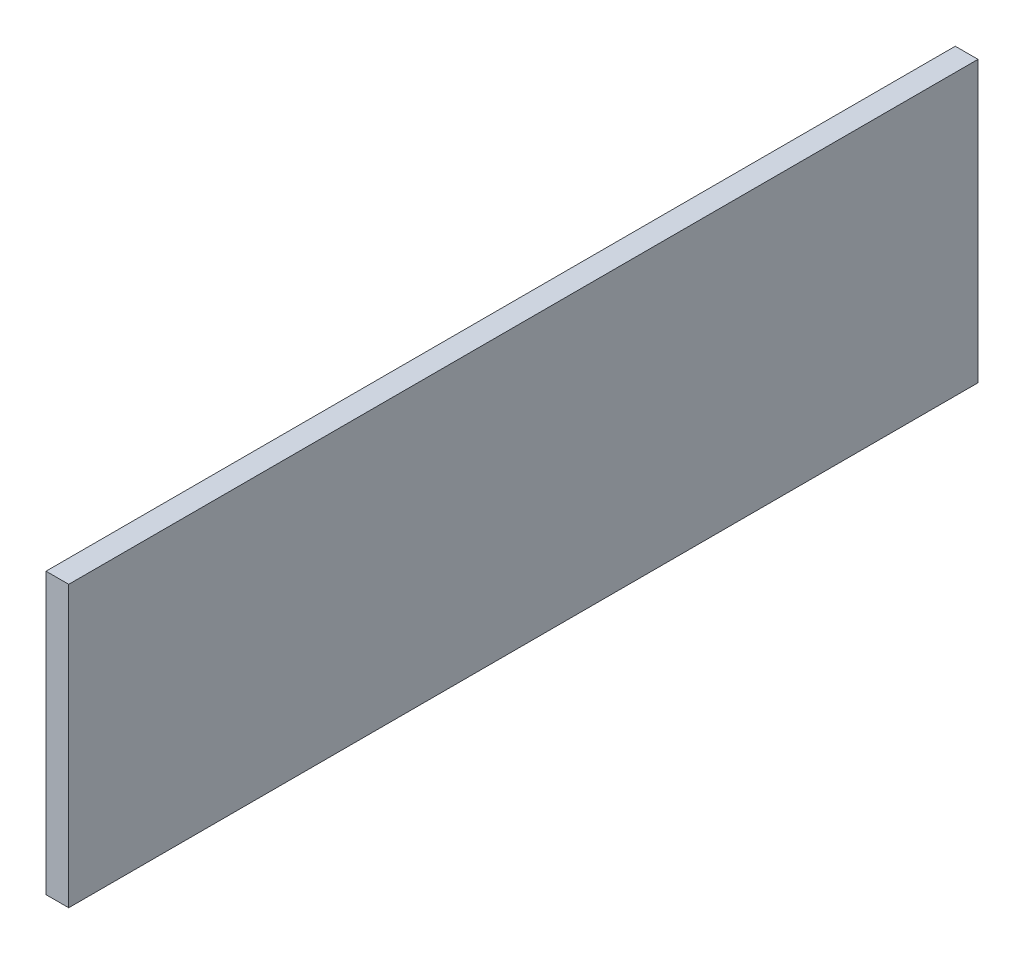
SolidWorks part; units mm, degrees
material "6061-T6 (SS)"
ref_plane "Front" through (0, 0, 0) normal (0, 0, 1) x (1, 0, 0)
ref_plane "Top" through (0, 0, 0) normal (0, 1, 0) x (1, 0, 0)
ref_plane "Right" through (0, 0, 0) normal (1, 0, 0) x (0, 0, -1)
sketch "Sketch1" plane through (0, 0, 0) normal (0, 0, 1) x (1, 0, 0)
  line L0 (-240.475, 9.525) -> (240.475, 9.525)
  line L1 (-250, 0) -> (250, 0)
  line L2 (-250, 0) -> (-250, 500)
  line L3 (-250, 500) -> (250, 500)
  line L4 (250, 0) -> (250, 500)
  line L5 (240.475, 9.525) -> (240.475, 490.475)
  line L6 (-240.475, 490.475) -> (240.475, 490.475)
  line L7 (-240.475, 9.525) -> (-240.475, 490.475)
  line L8 (-142.3043, 490.475) -> (-142.3043, 373.0167) construction
  line L9 (-240.475, 373.0167) -> (240.475, 373.0167)
  line L10 (-240.475, 373.0167) -> (-240.475, 363.4917)
  line L11 (-240.475, 363.4917) -> (240.475, 363.4917)
  line L12 (240.475, 373.0167) -> (240.475, 363.4917)
  line L13 (-240.475, 246.0333) -> (240.475, 246.0333)
  line L14 (-240.475, 246.0333) -> (-240.475, 236.5083)
  line L15 (-240.475, 236.5083) -> (240.475, 236.5083)
  line L16 (240.475, 246.0333) -> (240.475, 236.5083)
  line L17 (-240.475, 119.05) -> (240.475, 119.05)
  line L18 (-240.475, 119.05) -> (-240.475, 109.525)
  line L19 (-240.475, 109.525) -> (240.475, 109.525)
  line L20 (240.475, 119.05) -> (240.475, 109.525)
  line L21 (-142.3043, 363.4917) -> (-142.3043, 246.0333) construction
  line L22 (-142.3043, 236.5083) -> (-142.3043, 119.05) construction
  line L23 (-240.475, 431.7458) -> (-86.5083, 431.7458) construction
  line L24 (-86.5083, 490.475) -> (-76.9833, 490.475)
  line L25 (-86.5083, 490.475) -> (-86.5083, 373.0167)
  line L26 (-86.5083, 373.0167) -> (-76.9833, 373.0167)
  line L27 (-76.9833, 490.475) -> (-76.9833, 373.0167)
  line L28 (76.9833, 490.475) -> (86.5083, 490.475)
  line L29 (76.9833, 490.475) -> (76.9833, 373.0167)
  line L30 (76.9833, 373.0167) -> (86.5083, 373.0167)
  line L31 (86.5083, 490.475) -> (86.5083, 373.0167)
  line L32 (-76.9833, 431.7458) -> (76.9833, 431.7458) construction
  line L33 (86.5083, 431.7458) -> (240.475, 431.7458) construction
  line L34 (-131.311, 490.475) -> (-131.311, 363.4917) construction
  dimension "D1" = 500
  dimension "D2" = 9.525
  dimension "D3" = 9.525
  dimension "D4" = 100
  dimension "D5" = 9.525
  dimension "D6" = 117.4583
  dimension "D7" = 117.4583
  dimension "D8" = 126.9833
extrude "Boss-Extrude1" add sketch "Sketch1" along normal blind 381.25 contours L27 L6 L25 L9 | L17 L20 L19 L18
